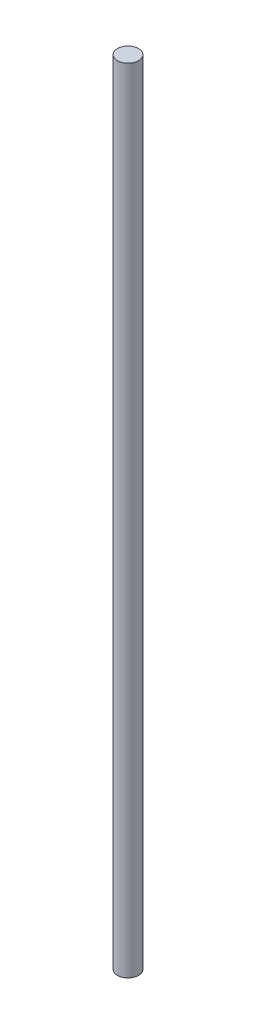
SolidWorks part; units mm, degrees
material "Hexcel AS4C (3000 Filaments)"
ref_plane "Front Plane" through (0, 0, 0) normal (0, 0, 1) x (1, 0, 0)
ref_plane "Top Plane" through (0, 0, 0) normal (0, 1, 0) x (1, 0, 0)
ref_plane "Right Plane" through (0, 0, 0) normal (1, 0, 0) x (0, 0, -1)
sketch "Sketch1" plane through (0, 0, 0) normal (0, 1, 0) x (1, 0, 0)
  circle A0 centre (0, 0) radius 2
  dimension "D1" = 4
extrude "Boss-Extrude1" add sketch "Sketch1" along normal blind 150
